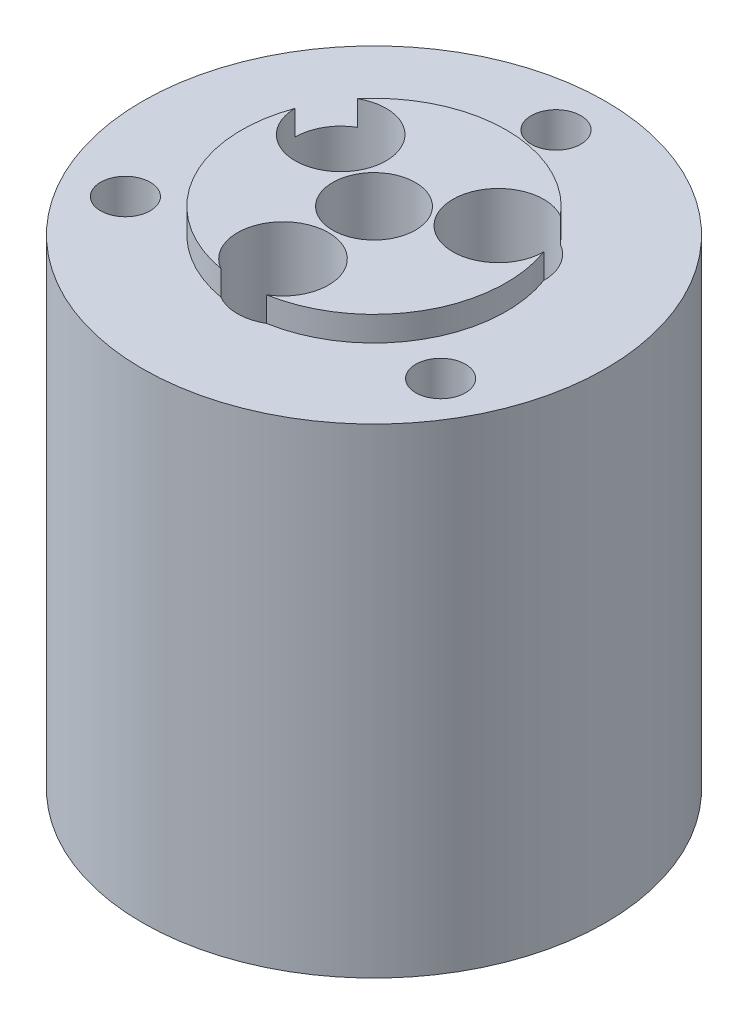
SolidWorks part; units mm, degrees
ref_plane "Plan de face" through (0, 0, 0) normal (0, 0, 1) x (1, 0, 0)
ref_plane "Plan de dessus" through (0, 0, 0) normal (0, 1, 0) x (1, 0, 0)
ref_plane "Plan de droite" through (0, 0, 0) normal (1, 0, 0) x (0, 0, -1)
sketch "Esquisse1" plane through (0, 0, 0) normal (0, 0, 1) x (1, 0, 0)
  line L0 (0, 0) -> (0, 32) construction
  line L1 (8, 0) -> (8, 1.5)
  line L2 (8, 1.5) -> (14, 1.5)
  line L3 (14, 1.5) -> (14, 30.5)
  line L4 (8, 0) -> (2.5, 0)
  line L7 (2.5, 0) -> (2.5, 32)
  line L8 (14, 16) -> (2.5, 16) construction
  line L9 (2.5, 16) -> (0, 16) construction
  line L12 (8, 32) -> (2.5, 32)
  line L13 (8, 30.5) -> (14, 30.5)
  line L14 (8, 32) -> (8, 30.5)
  dimension "D2" = 5
  dimension "D4" = 1.5
  dimension "D5" = 16
  dimension "D6" = 28
  dimension "D7" = 32
revolve "Révolution1" add sketch "Esquisse1" angle 360 about L0
sketch "Esquisse2" plane through (0, 30.5, 0) normal (0, 1, 0) x (1, 0, 0)
  circle A0 centre (0, 0) radius 11 construction
  circle A1 centre (0, 11) radius 1.5
  circle A2 centre (9.5263, -5.5) radius 1.5
  circle A3 centre (-9.5263, -5.5) radius 1.5
  point P11 (0, 0)
  dimension "D1" = 22
  dimension "D2" = 3
  dimension "D3" = 3
extrude "Enlèv. mat.-Extru.1" cut sketch "Esquisse2" against normal blind 10
sketch "Esquisse3" plane through (0, 1.5, 0) normal (0, -1, 0) x (1, 0, 0)
  circle A0 centre (0, 0) radius 5.5 construction
  circle A1 centre (0, 5.5) radius 1.5
  circle A2 centre (4.7631, -2.75) radius 1.5
  circle A3 centre (-4.7631, -2.75) radius 1.5
  point P12 (0, 0)
  dimension "D1" = 11
  dimension "D2" = 3
  dimension "D3" = 3
extrude "Enlèv. mat.-Extru.2" cut sketch "Esquisse3" against normal through all and the other way up to next
sketch "Esquisse4" plane through (0, 32, 0) normal (0, -1, 0) x (1, 0, 0)
  circle A0 centre (0, 5.5) radius 2.75
  circle A1 centre (4.7631, -2.75) radius 2.75
  circle A3 centre (-4.7631, -2.75) radius 2.75
  dimension "D1" = 5.5
extrude "Enlèv. mat.-Extru.7" cut sketch "Esquisse4" along normal blind 20
sketch "Esquisse5" plane through (0, 0, 0) normal (0, -1, 0) x (1, 0, 0)
  circle A0 centre (0, 0) radius 8
extrude "Enlèv. mat.-Extru.8" cut sketch "Esquisse5" against normal blind 8
